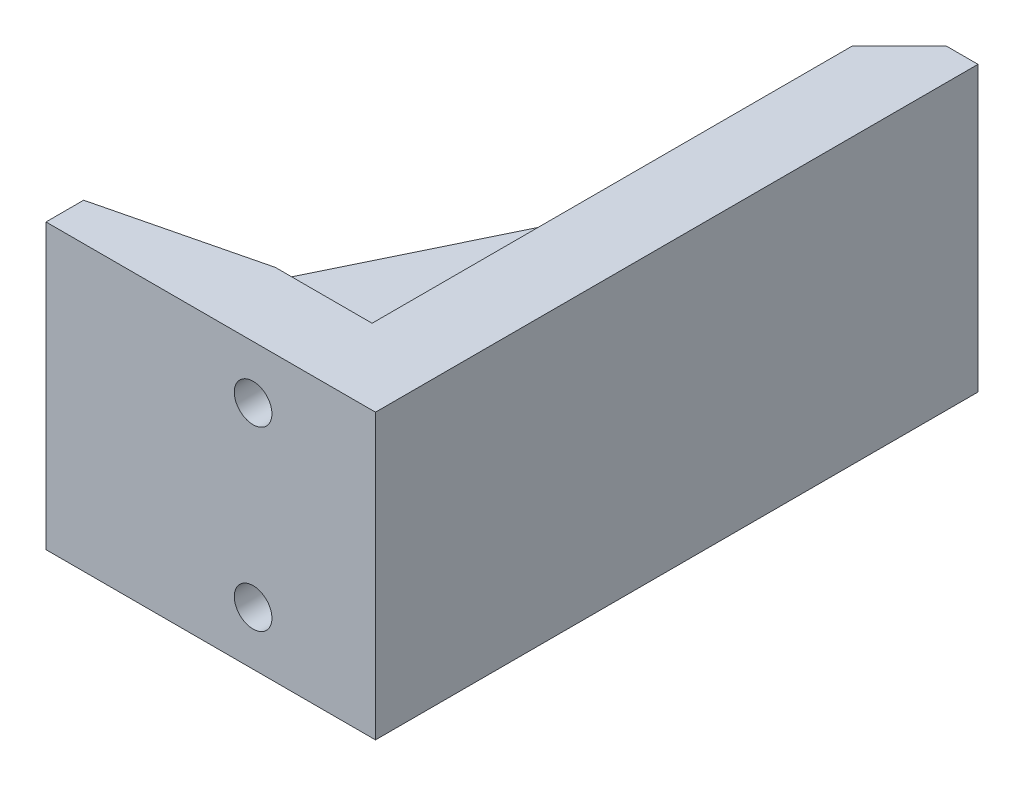
SolidWorks part; units mm, degrees
ref_plane "Front Plane" through (0, 0, 0) normal (0, 0, 1) x (1, 0, 0)
ref_plane "Top Plane" through (0, 0, 0) normal (0, 1, 0) x (1, 0, 0)
ref_plane "Right Plane" through (0, 0, 0) normal (1, 0, 0) x (0, 0, -1)
sketch "Sketch1" plane through (0, 0, 0) normal (0, 0, 1) x (1, 0, 0)
  line L1 (0, 0) -> (17.145, 0)
  line L2 (0, 0) -> (0, -17.145)
  line L3 (0, -17.145) -> (17.145, -17.145)
  line L4 (17.145, 0) -> (17.145, -17.145)
  dimension "D1" = 17.145
  dimension "D2" = 17.145
extrude "Boss-Extrude1" add sketch "Sketch1" along normal blind 5.08
sketch "Sketch2" plane through (0, 0, 0) normal (0, 0, -1) x (-1, 0, 0)
  line L0 (-8.89, 0) -> (-8.89, -17.145) construction
  line L1 (-17.145, 0) -> (0, 0) construction
  line L2 (0, -17.145) -> (-17.145, -17.145) construction
  line L3 (0, 0) -> (0, -17.145) construction
  circle A0 centre (-8.89, -2.5908) radius 1.27
  circle A1 centre (-8.89, -14.5288) radius 1.27
  dimension "D1" = 11.938
  dimension "D2" = 2.54
  dimension "D3" = 2.54
  dimension "D4" = 2.6162
  dimension "D5" = 2.5908
  dimension "D6" = 8.89
extrude "Cut-Extrude1" cut sketch "Sketch2" against normal through all
sketch "Sketch3" plane through (0, 0, 0) normal (0, 0, -1) x (-1, 0, 0)
  circle A0 centre (-8.89, -2.5908) radius 2.54
  circle A1 centre (-8.89, -14.5288) radius 2.54
  dimension "D1" = 5.08
  dimension ".2" = 5.08
extrude "Cut-Extrude4" cut sketch "Sketch3" against normal blind 2.54
sketch "Sketch4" plane through (0, 0, 0) normal (0, 0, -1) x (-1, 0, 0)
  line L0 (0, -17.145) -> (-17.145, -17.145) construction
  line L1 (0, 0) -> (-6.3077, 0)
  line L2 (0, 0) -> (0, -17.145)
  line L3 (0, -17.145) -> (-6.3077, -17.145)
  line L4 (-6.3077, 0) -> (-6.3077, -17.145)
extrude "Boss-Extrude2" add sketch "Sketch4" along normal blind 17.78
sketch "Sketch5" plane through (0, 0, 0) normal (-1, 0, 0) x (0, 0, 1)
  line L0 (5.08, -17.145) -> (-17.78, -17.145) construction
  line L1 (5.08, 0) -> (2.54, 0)
  line L2 (5.08, 0) -> (5.08, -17.145)
  line L3 (5.08, -17.145) -> (2.54, -17.145)
  line L4 (2.54, 0) -> (2.54, -17.145)
  dimension "D1" = 2.54
extrude "Boss-Extrude3" add sketch "Sketch5" along normal blind 5.08
chamfer "Chamfer1" distance 3.175 angle 45 1 edges at (0, -8.5725, -17.78)
sketch "Sketch7" plane through (0, 0, 0) normal (0, 1, 0) x (1, 0, 0)
  line L0 (-5.08, -2.54) -> (0, 14.605)
  line L1 (0, 14.605) -> (0, -2.54)
  line L2 (0, -2.54) -> (-5.08, -2.54)
extrude "Boss-Extrude4" add sketch "Sketch7" against normal blind 2.54
sketch "Sketch8" plane through (0, -17.145, 0) normal (0, -1, 0) x (1, 0, 0)
  line L3 (0, 2.54) -> (-5.08, 2.54)
  line L4 (-5.08, 2.54) -> (0, -14.605)
  line L5 (0, -14.605) -> (0, 2.54)
  line L6 (0, 2.54) -> (-5.08, 2.54)
  line L7 (-5.08, 2.54) -> (0, -14.605)
  line L8 (0, -14.605) -> (0, 2.54)
  dimension "D1" = 0
extrude "Boss-Extrude5" add sketch "Sketch8" against normal blind 2.54
sketch "Sketch9" plane through (0, 0, -17.78) normal (0, 0, -1) x (-1, 0, 0)
  line L0 (-6.3077, -17.145) -> (-3.175, -17.145) construction
  line L1 (-6.3077, 0) -> (-5.3077, 0)
  line L2 (-6.3077, 0) -> (-6.3077, -17.145)
  line L3 (-6.3077, -17.145) -> (-5.3077, -17.145)
  line L4 (-5.3077, 0) -> (-5.3077, -17.145)
  dimension "D1" = 1
extrude "Cut-Extrude5" cut sketch "Sketch9" against normal up to surface (17.78 mm away) up to face at (6.35, -2.5908, 0)
sketch "草图1" plane through (0, 0, 0) normal (0, 1, 0) x (1, 0, 0)
  line L8 (17.145, 0) -> (5.3077, 0)
  line L9 (5.3077, 0) -> (5.3077, 17.78)
  line L10 (5.3077, 17.78) -> (3.175, 17.78)
  line L11 (3.175, 17.78) -> (0, 14.605)
  line L12 (0, 14.605) -> (-5.08, -2.54)
  line L13 (-5.08, -2.54) -> (-5.08, -5.08)
  line L14 (-5.08, -5.08) -> (17.145, -5.08)
  line L15 (17.145, -5.08) -> (17.145, 0)
  line L16 (17.145, 0) -> (5.3077, 0)
  line L17 (5.3077, 0) -> (5.3077, 17.78)
  line L18 (5.3077, 17.78) -> (3.175, 17.78)
  line L19 (3.175, 17.78) -> (0, 14.605)
  line L20 (0, 14.605) -> (-5.08, -2.54)
  line L21 (-5.08, -2.54) -> (-5.08, -5.08)
  line L22 (-5.08, -5.08) -> (17.145, -5.08)
  line L23 (17.145, -5.08) -> (17.145, 0)
  dimension "D1" = 0
extrude "凸台-拉伸1" add sketch "草图1" along normal blind 1
sketch "草图2" plane through (0, -17.145, 0) normal (0, -1, 0) x (1, 0, 0)
  line L8 (5.3077, -17.78) -> (5.3077, 0)
  line L9 (5.3077, 0) -> (17.145, 0)
  line L10 (17.145, 0) -> (17.145, 5.08)
  line L11 (17.145, 5.08) -> (-5.08, 5.08)
  line L12 (-5.08, 5.08) -> (-5.08, 2.54)
  line L13 (-5.08, 2.54) -> (0, -14.605)
  line L14 (0, -14.605) -> (3.175, -17.78)
  line L15 (3.175, -17.78) -> (5.3077, -17.78)
  line L16 (5.3077, -17.78) -> (5.3077, 0)
  line L17 (5.3077, 0) -> (17.145, 0)
  line L18 (17.145, 0) -> (17.145, 5.08)
  line L19 (17.145, 5.08) -> (-5.08, 5.08)
  line L20 (-5.08, 5.08) -> (-5.08, 2.54)
  line L21 (-5.08, 2.54) -> (0, -14.605)
  line L22 (0, -14.605) -> (3.175, -17.78)
  line L23 (3.175, -17.78) -> (5.3077, -17.78)
  dimension "D1" = 0
extrude "凸台-拉伸2" add sketch "草图2" along normal blind 1
sketch "草图3" plane through (17.145, 0, 0) normal (1, 0, 0) x (0, 0, -1)
  line L0 (17.78, -18.145) -> (35.56, -18.145)
  line L1 (35.56, -18.145) -> (35.56, 1)
  line L2 (35.56, 1) -> (17.78, 1)
  line L4 (0, 1) -> (0, -18.145)
  line L5 (0, -18.145) -> (17.78, -18.145)
  line L6 (17.78, -18.145) -> (17.78, 1)
  line L7 (17.78, 1) -> (0, 1)
  line L8 (0, 1) -> (0, -18.145)
  line L9 (0, -18.145) -> (17.78, -18.145)
  line L11 (17.78, 1) -> (0, 1)
  dimension "D2" = 17.78
  dimension "D1" = 0
extrude "凸台-拉伸3" add sketch "草图3" against normal blind 5.31
sketch "草图4" plane through (0, 1, 0) normal (0, 1, 0) x (1, 0, 0)
  line L0 (17.145, 35.56) -> (15.015, 35.56) construction
  line L1 (11.835, 35.56) -> (17.145, 35.56) construction
  line L2 (15.015, 35.56) -> (11.835, 32.38)
  line L3 (11.835, 35.56) -> (11.835, 0) construction
  line L5 (15.015, 35.56) -> (11.835, 35.56)
  line L6 (11.835, 35.56) -> (11.835, 32.38)
  dimension "D1" = 2.13
  dimension "D2" = 45
extrude "切除-拉伸1" cut sketch "草图4" against normal through all
sketch "草图5" plane through (0, 1, 0) normal (0, 1, 0) x (1, 0, 0)
  line L1 (0, 14.605) -> (-5.08, -2.54) construction
  line L2 (3.175, 17.78) -> (0, 14.605) construction
  line L3 (5.3077, 17.78) -> (3.175, 17.78) construction
  line L4 (5.3077, 0) -> (5.3077, 17.78) construction
  line L5 (0, 14.605) -> (-5.08, -2.54)
  line L6 (3.175, 17.78) -> (0, 14.605)
  line L7 (5.3077, 17.78) -> (3.175, 17.78)
  line L8 (5.3077, 0) -> (5.3077, 17.78)
  line L9 (-5.08, -2.54) -> (5.3077, -2.54)
  line L10 (5.3077, -2.54) -> (5.3077, 0)
extrude "切除-拉伸2" cut sketch "草图5" against normal through all
ref_plane "基准面1" through (0, -8.57, 0) normal (0, -1, 0) x (-1, 0, 0)
sketch "草图6" plane through (0, -8.57, 0) normal (0, -1, 0) x (-1, 0, 0)
  line L0 (-11.835, 0) -> (-11.835, 32.38) construction
  line L1 (-5.3077, 0) -> (-11.835, 0) construction
  line L2 (-5.3077, -2.54) -> (-5.3077, 0) construction
  line L3 (5.08, -2.54) -> (-5.3077, -2.54) construction
  line L4 (-11.835, 0) -> (-11.835, 32.38)
  line L5 (-5.3077, 0) -> (-11.835, 0)
  line L6 (-5.3077, -2.54) -> (-5.3077, 0)
  line L7 (5.08, -2.54) -> (-5.3077, -2.54)
  line L8 (-11.835, 32.38) -> (5.08, -2.54)
extrude "凸台-拉伸4" add sketch "草图6" along normal mid plane 5.31
sketch "草图7" plane through (0, -5.915, 0) normal (0, 1, 0) x (1, 0, 0)
  line L0 (5.3077, -2.54) -> (-5.08, -2.54) construction
  line L1 (5.3077, 0) -> (5.3077, -2.54) construction
  line L2 (5.3077, -2.54) -> (-5.08, -2.54)
  line L3 (5.3077, 0) -> (5.3077, -2.54)
  line L4 (5.3077, 0) -> (-5.08, -2.54)
extrude "凸台-拉伸5" add sketch "草图7" along normal up to surface (6.915 mm away) up to face at (8.1589, 1, -9.8067)
sketch "草图8" plane through (0, -11.225, 0) normal (0, -1, 0) x (1, 0, 0)
  line L0 (-5.08, 2.54) -> (5.3077, 2.54) construction
  line L1 (5.3077, 2.54) -> (5.3077, 0) construction
  line L2 (-5.08, 2.54) -> (5.3077, 2.54)
  line L3 (5.3077, 2.54) -> (5.3077, 0)
  line L4 (5.3077, 0) -> (-5.08, 2.54)
extrude "凸台-拉伸6" add sketch "草图8" along normal up to surface (6.92 mm away) up to face at (8.1589, -18.145, -9.8067)
